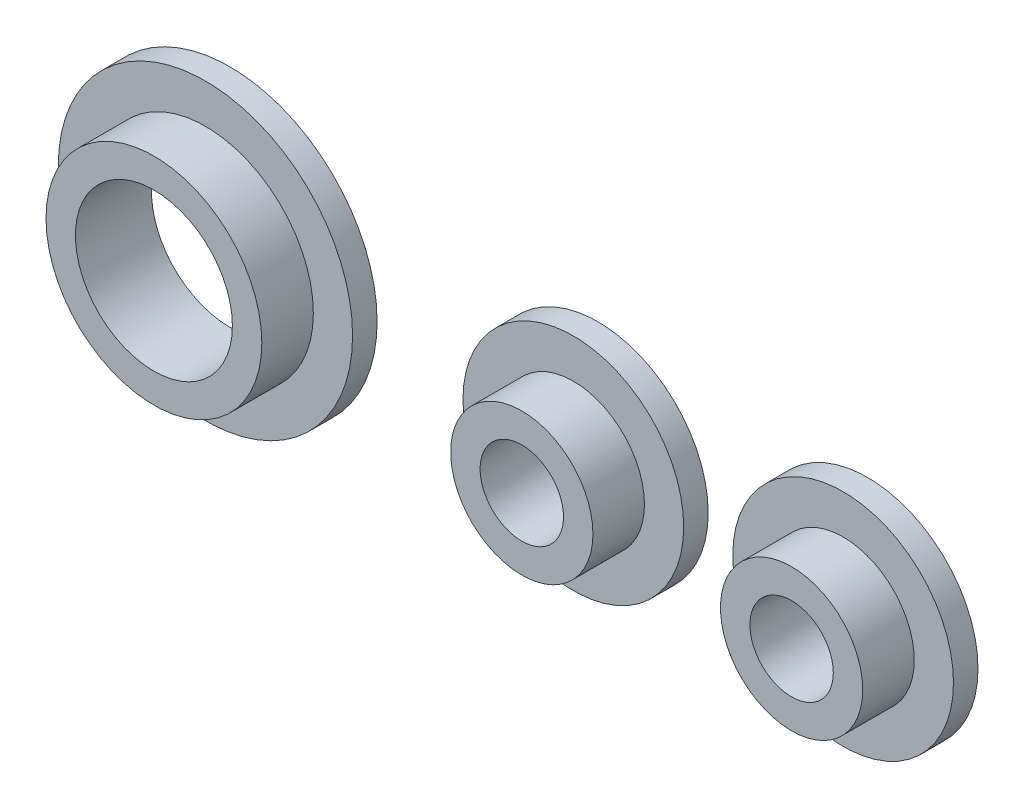
SolidWorks part; units mm, degrees
ref_plane "Front Plane" through (0, 0, 0) normal (0, 0, 1) x (1, 0, 0)
ref_plane "Top Plane" through (0, 0, 0) normal (0, 1, 0) x (1, 0, 0)
ref_plane "Right Plane" through (0, 0, 0) normal (1, 0, 0) x (0, 0, -1)
sketch "Sketch1" plane through (0, 0, 0) normal (0, 0, 1) x (1, 0, 0)
  circle A0 centre (0, 0) radius 12
  circle A1 centre (30, 0) radius 9
  circle A2 centre (52, 0) radius 9
extrude "Lips" add sketch "Sketch1" along normal blind 2
ref_plane "Plane_Z+2.00" through (0, 0, 2) normal (0, 0, 1) x (1, 0, 0)
sketch "Sketch2" plane through (0, 0, 2) normal (0, 0, 1) x (1, 0, 0)
  circle A0 centre (0, 0) radius 8.8
  circle A1 centre (30, 0) radius 5.8
  circle A2 centre (52, 0) radius 5.8
extrude "Necks" add sketch "Sketch2" along normal blind 4.2
sketch "Sketch3" plane through (0, 0, 0) normal (0, 0, 1) x (1, 0, 0)
  circle A0 centre (0, 0) radius 6.4
  circle A1 centre (30, 0) radius 3.4
  circle A2 centre (52, 0) radius 3.4
extrude "Cable_bores" cut sketch "Sketch3" against normal through all and the other way through all
